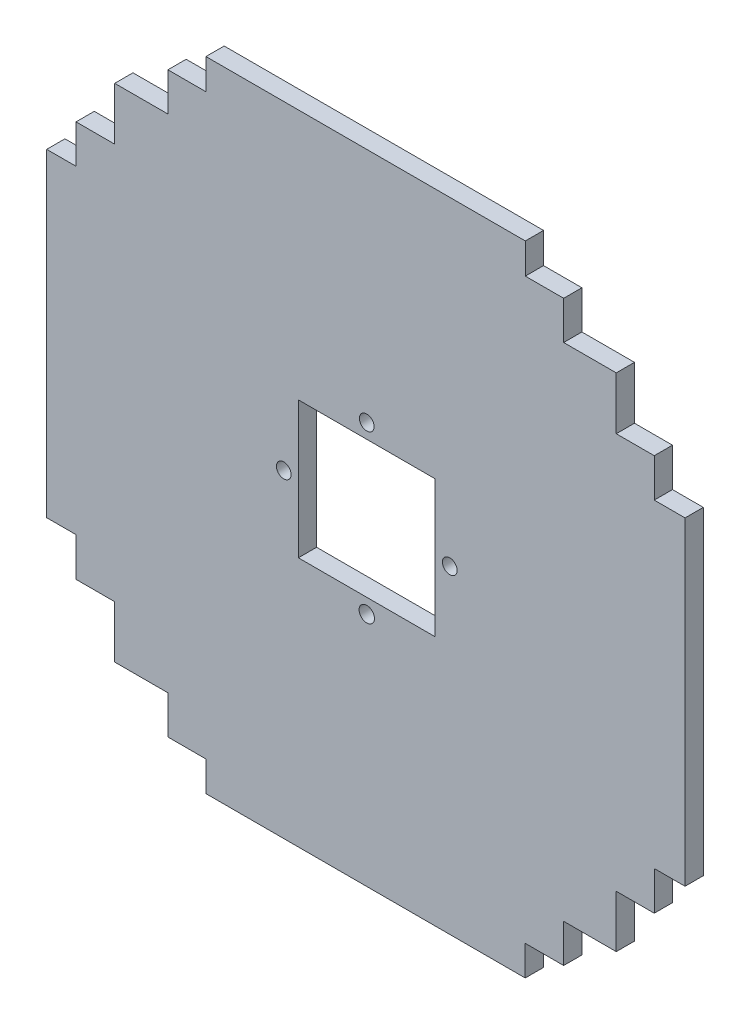
SolidWorks part; units mm, degrees
ref_plane "Front Plane" through (0, 0, 0) normal (0, 0, 1) x (1, 0, 0)
ref_plane "Top Plane" through (0, 0, 0) normal (0, 1, 0) x (1, 0, 0)
ref_plane "Right Plane" through (0, 0, 0) normal (1, 0, 0) x (0, 0, -1)
sketch "Sketch1" plane through (0, 0, 0) normal (0, 0, 1) x (1, 0, 0)
  line L1 (-83.0148, 130.4206) -> (5.9431, 130.4206)
  line L2 (-127.3639, 85.8601) -> (-127.3639, -2.998)
  line L3 (-83.0375, -47.3794) -> (5.9204, -47.3794)
  line L4 (50.4361, 85.8601) -> (50.4361, -2.998)
  line L5 (-57.2655, 60.4811) -> (-19.1655, 60.4811)
  line L6 (-57.2655, 60.4811) -> (-57.2655, 22.3811)
  line L7 (-127.3639, 85.8601) -> (-119.1922, 85.8601)
  line L8 (-83.0148, 130.4206) -> (-83.0148, 121.9303)
  line L9 (-93.602, 111.2601) -> (-108.4148, 111.2601)
  line L10 (-108.4148, 96.5761) -> (-108.4148, 111.2601)
  line L11 (-127.3639, -2.998) -> (-119.1922, -2.998)
  line L12 (-83.0375, -47.3794) -> (-83.0375, -39.0155)
  line L13 (-57.2655, 22.3811) -> (-19.1655, 22.3811)
  line L14 (-19.1655, 60.4811) -> (-19.1655, 22.3811)
  line L15 (50.4361, -2.998) -> (41.8555, -2.998)
  line L16 (5.9204, -47.3794) -> (5.9204, -39.0155)
  line L17 (-93.602, -28.348) -> (-108.4148, -28.348)
  line L18 (-108.4148, -13.786) -> (-108.4148, -28.348)
  line L19 (50.4361, 85.8601) -> (41.8555, 85.8601)
  line L20 (5.9431, 130.4206) -> (5.9431, 121.9303)
  line L23 (16.626, -28.348) -> (31.2696, -28.348)
  line L24 (31.2696, -13.786) -> (31.2696, -28.348)
  line L27 (16.626, 111.2601) -> (31.2696, 111.2601)
  line L28 (31.2696, 96.5761) -> (31.2696, 111.2601)
  line L31 (-83.0148, 121.9303) -> (-93.602, 121.9303)
  line L32 (-93.602, 111.2601) -> (-93.602, 121.9303)
  line L35 (-108.4148, 96.5761) -> (-119.1922, 96.5761)
  line L36 (-119.1922, 85.8601) -> (-119.1922, 96.5761)
  line L39 (-108.4148, -13.786) -> (-119.1922, -13.786)
  line L40 (-119.1922, -2.998) -> (-119.1922, -13.786)
  line L43 (-83.0375, -39.0155) -> (-93.602, -39.0155)
  line L44 (-93.602, -28.348) -> (-93.602, -39.0155)
  line L47 (5.9204, -39.0155) -> (16.626, -39.0155)
  line L48 (16.626, -28.348) -> (16.626, -39.0155)
  line L51 (31.2696, -13.786) -> (41.8555, -13.786)
  line L52 (41.8555, -2.998) -> (41.8555, -13.786)
  line L55 (31.2696, 96.5761) -> (41.8555, 96.5761)
  line L56 (41.8555, 85.8601) -> (41.8555, 96.5761)
  line L59 (5.9431, 121.9303) -> (16.626, 121.9303)
  line L60 (16.626, 111.2601) -> (16.626, 121.9303)
  circle A0 centre (-61.3295, 41.4311) radius 2.0457
  circle A1 centre (-38.2155, 64.5451) radius 2.0457
  circle A2 centre (-15.1015, 41.4311) radius 2.0457
  circle A3 centre (-38.2155, 18.3171) radius 2.1334
  point P1 (-38.2155, 41.4311)
extrude "Boss-Extrude3" add sketch "Sketch1" along normal blind 5.08
